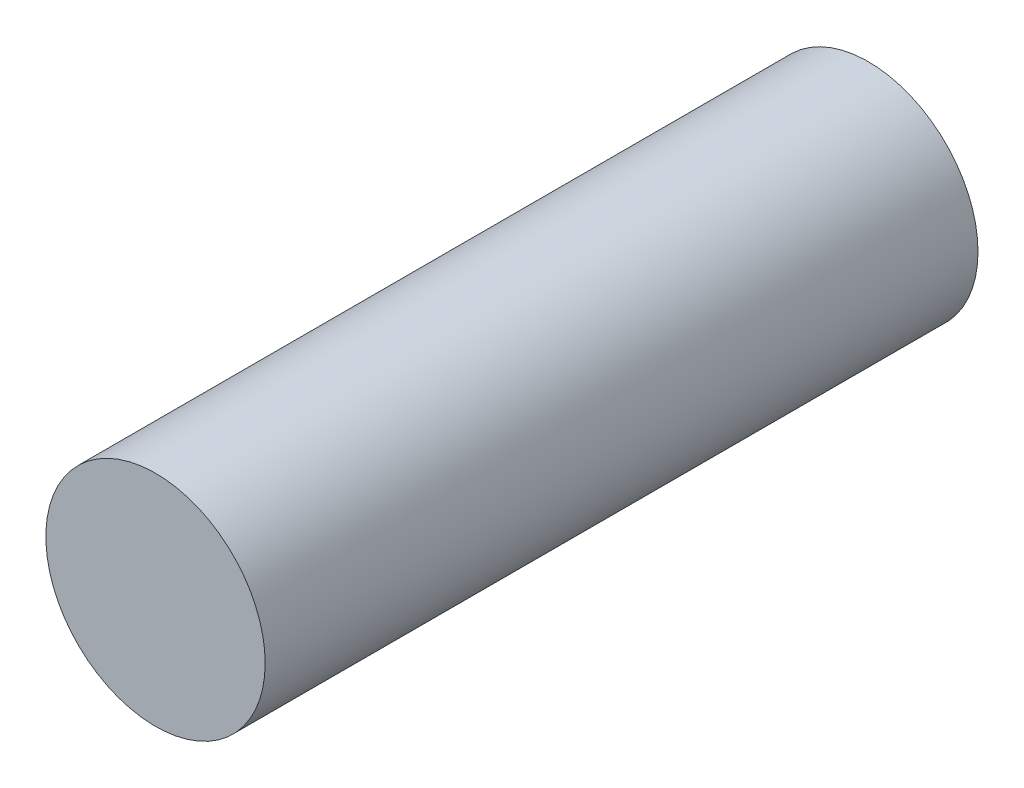
SolidWorks part; units mm, degrees
ref_plane "Front Plane" through (0, 0, 0) normal (0, 0, 1) x (1, 0, 0)
ref_plane "Top Plane" through (0, 0, 0) normal (0, 1, 0) x (1, 0, 0)
ref_plane "Right Plane" through (0, 0, 0) normal (1, 0, 0) x (0, 0, -1)
sketch "Sketch1" plane through (0, 0, 0) normal (0, 0, 1) x (1, 0, 0)
  circle A0 centre (0, 0) radius 20
  dimension "D1" = 40
extrude "Boss-Extrude1" add sketch "Sketch1" along normal blind 130
